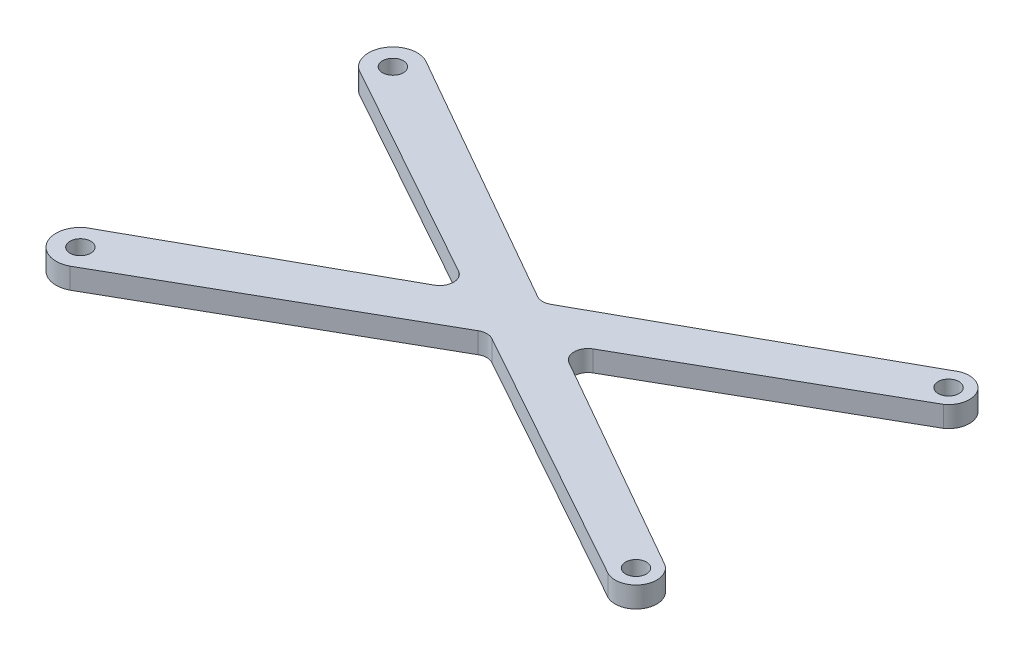
SolidWorks part; units mm, degrees
material "1060 Alloy"
ref_plane "Front Plane" through (0, 0, 0) normal (0, 0, 1) x (1, 0, 0)
ref_plane "Top Plane" through (0, 0, 0) normal (0, 1, 0) x (1, 0, 0)
ref_plane "Right Plane" through (0, 0, 0) normal (1, 0, 0) x (0, 0, -1)
sketch "Sketch1" plane through (0, 0, 0) normal (0, 1, 0) x (1, 0, 0)
  line L0 (0, 45) -> (80, 0) construction
  line L1 (0, 0) -> (80, 0) construction
  line L2 (0, 0) -> (0, 45) construction
  line L3 (0, 45) -> (80, 45) construction
  line L4 (80, 0) -> (80, 45) construction
  line L5 (1.6224, 48.1012) -> (39.0534, 26.7717)
  line L6 (-2.106, 42.2045) -> (30.2026, 24.2481)
  line L7 (0, 0) -> (80, 45) construction
  line L8 (-2.106, 2.7955) -> (30.2026, 20.7519)
  line L9 (1.6224, -3.1012) -> (39.0534, 18.2283)
  line L10 (41.0151, 26.7612) -> (78.6717, 47.6899)
  line L11 (49.5992, 20.7623) -> (81.7142, 2.462)
  line L12 (49.5992, 24.2377) -> (81.7142, 42.538)
  line L13 (41.0151, 18.2388) -> (78.6717, -2.6899)
  line L15 (46.1173, 25.941) -> (33.8827, 25.941) construction
  line L16 (46.1173, 25.941) -> (46.1173, 19.059) construction
  line L17 (46.1173, 19.059) -> (33.8827, 19.059) construction
  line L18 (33.8827, 25.941) -> (33.8827, 19.059) construction
  line L19 (46.1173, 25.941) -> (33.8827, 19.059) construction
  line L20 (46.1173, 19.059) -> (33.8827, 25.941) construction
  arc A0 (1.6224, 48.1012) -> (-2.106, 42.2045) centre (0, 45) ccw
  arc A1 (78.6717, -2.6899) -> (81.7142, 2.462) centre (80, 0) ccw
  arc A2 (-2.106, 2.7955) -> (1.6224, -3.1012) centre (0, 0) ccw
  arc A3 (81.7142, 42.538) -> (78.6717, 47.6899) centre (80, 45) ccw
  circle A4 centre (0, 45) radius 1.5
  circle A5 centre (80, 45) radius 1.5
  circle A6 centre (80, 0) radius 1.5
  circle A7 centre (0, 0) radius 1.5
  arc A8 (39.0534, 18.2283) -> (41.0151, 18.2388) centre (40.0436, 16.4906) cw
  arc A9 (41.0151, 26.7612) -> (39.0534, 26.7717) centre (40.0436, 28.5094) cw
  arc A10 (49.5992, 20.7623) -> (49.5992, 24.2377) centre (50.5894, 22.5) cw
  arc A11 (30.2026, 20.7519) -> (30.2026, 24.2481) centre (29.231, 22.5) ccw
  point P5 (40, 22.5)
  point P10 (40, 22.5)
  point P16 (40, 22.5)
  point P30 (40.0313, 18.7855)
  point P33 (40.0313, 26.2145)
  point P36 (46.5498, 22.5)
  point P39 (33.348, 22.5)
  dimension "D3" = 3.5
  dimension "D4" = 3.5
  dimension "D5" = 3
  dimension "D6" = 3
  dimension "D10" = 3
  dimension "D11" = 2
  dimension "D1" = 45
  dimension "D2" = 80
  dimension "D7" = 40.5618
  dimension "D8" = 44.2072
  dimension "D9" = 6.8819
extrude "Boss-Extrude1" add sketch "Sketch1" along normal blind 3
